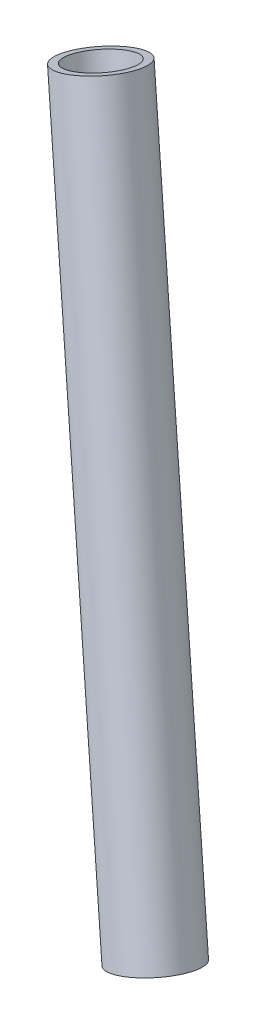
SolidWorks part; units mm, degrees
ref_plane "Front Plane" through (0, 0, 0) normal (0, 0, 1) x (1, 0, 0)
ref_plane "Top Plane" through (0, 0, 0) normal (0, 1, 0) x (1, 0, 0)
ref_plane "Right Plane" through (0, 0, 0) normal (1, 0, 0) x (0, 0, -1)
sketch3d "3DSketch1"
  line L0 (3250.36, 620.6, 442.71) -> (3353.94, 263.22, 515.22) construction
  line L1 (3261.9813, 580.5034, 450.8453) -> (3342.3187, 303.3166, 507.0847)
  point P0 (3353.94, 263.22, 515.22)
  point P2 (3250.36, 620.6, 442.71)
  point P7 (3302.15, 441.91, 478.965)
other "Pipe 1.0 SCH 40(1)"
ref_plane "Plane1" through (3261.9813, 580.5034, 450.8453) normal (0.2732, -0.9427, 0.1913) x (0.9373, 0.2162, -0.2732)
sketch "Sketch1" plane through (3261.9813, 580.5034, 450.8453) normal (0.2732, -0.9427, 0.1913) x (0.9373, 0.2162, -0.2732)
  circle A0 centre (0, 0) radius 13.3223
  circle A1 centre (0, 0) radius 16.7005
  circle A2 centre (0, 0) radius 12.7 construction
  point P5 (0, 0)
  dimension "In_dia" = 26.6446
  dimension "Out_dia" = 33.401
  dimension "D1" = 25.4
